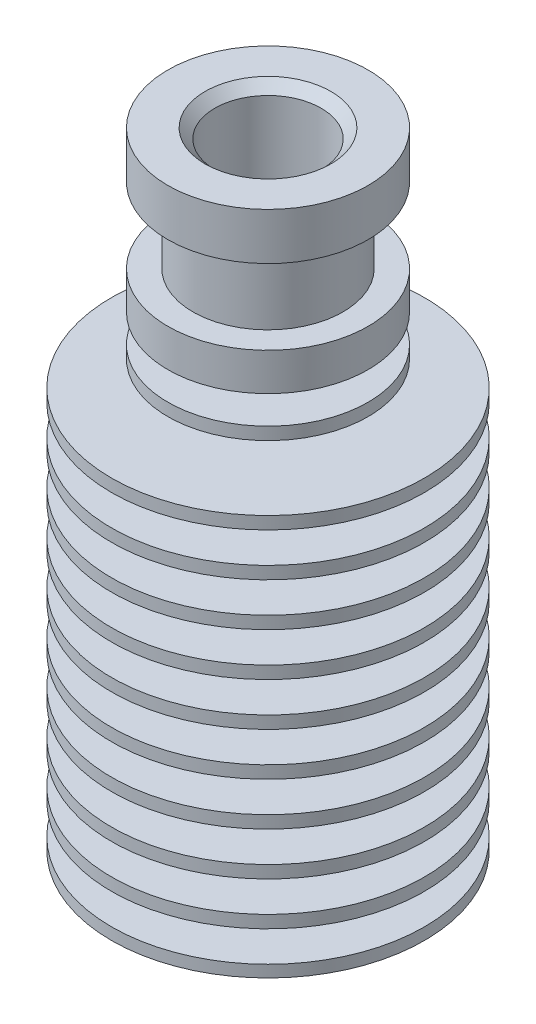
SolidWorks part; units mm, degrees
material "Stop 1060"
ref_plane "Płaszczyzna przednia" through (0, 0, 0) normal (0, 0, 1) x (1, 0, 0)
ref_plane "Płaszczyzna górna" through (0, 0, 0) normal (0, 1, 0) x (1, 0, 0)
ref_plane "Płaszczyzna prawa" through (0, 0, 0) normal (1, 0, 0) x (0, 0, -1)
sketch "Szkic1" plane through (0, 0, 0) normal (0, 0, 1) x (1, 0, 0)
  line L0 (0, 0) -> (-12.5, 0)
  line L1 (-12.5, 0) -> (-12.5, 32)
  line L2 (-12.5, 32) -> (-8, 32)
  line L3 (-8, 32) -> (-8, 50)
  line L4 (-8, 50) -> (0, 50)
  line L5 (0, 50) -> (0, 0)
  line L6 (0, 50) -> (0, 0) construction
  dimension "D1" = 50
  dimension "D2" = 32
  dimension "D3" = 12.5
  dimension "D4" = 8
revolve "Obrót1" add sketch "Szkic1" angle 360 about L6
sketch "Szkic2" plane through (0, 0, 0) normal (0, 0, 1) x (1, 0, 0)
  line L0 (-8, 46.25) -> (-6, 46.25)
  line L1 (-8, 50) -> (-8, 32) construction
  line L2 (0, 46.25) -> (0, 40.25) construction
  line L3 (-6, 40.25) -> (-8, 40.25)
  line L4 (-8, 40.25) -> (-8, 46.25)
  line L5 (8, 50) -> (-8, 50) construction
  line L6 (-6, 46.25) -> (-6, 40.25)
  line L7 (0, 46.25) -> (-6, 46.25) construction
  line L8 (-6, 40.25) -> (0, 40.25) construction
  dimension "D1" = 3.75
  dimension "D2" = 6
  dimension "D3" = 6
revolve "Wycięcie-obrót1" cut sketch "Szkic2" angle 360 about L2
sketch "Szkic3" plane through (0, 0, 0) normal (0, 0, 1) x (1, 0, 0)
  line L0 (-8, 37.25) -> (-4.5, 37.25)
  line L1 (-8, 40.25) -> (-8, 32) construction
  line L2 (-4.5, 37.25) -> (-4.5, 35)
  line L3 (-4.5, 35) -> (-8, 35)
  line L4 (-8, 34) -> (-4.5, 34)
  line L5 (-4.5, 34) -> (-4.5, 32)
  line L6 (12.5, 32) -> (-12.5, 32) construction
  line L7 (-4.5, 32) -> (-8, 32)
  line L8 (-8, 32) -> (-8, 34)
  line L9 (0, 32) -> (0, 40.25) construction
  line L10 (8, 40.25) -> (-8, 40.25) construction
  line L11 (-8, 37.25) -> (-8, 35)
  dimension "D1" = 3
  dimension "D2" = 2.25
  dimension "D3" = 1
  dimension "D4" = 4.5
revolve "Wycięcie-obrót2" cut sketch "Szkic3" angle 360 about L9
sketch "Szkic4" plane through (0, 0, 0) normal (0, 0, 1) x (1, 0, 0)
  line L0 (0, 0) -> (0, 32) construction
  line L1 (12.5, 32) -> (-12.5, 32) construction
  line L2 (-4.5, 31) -> (-12.5, 31)
  line L3 (-12.5, 32) -> (-12.5, 0) construction
  line L4 (-12.5, 31) -> (-12.5, 28.55)
  line L5 (-12.5, 28.55) -> (-4.5, 28.55)
  line L6 (-4.5, 31) -> (-4.5, 28.55)
  line L7 (-4.5, 34) -> (-4.5, 32) construction
  line L8 (-4.5, 31) -> (0, 31) construction
  line L9 (-4.5, 28.55) -> (0, 28.55) construction
  line L10 (-12.5, 25.1) -> (-4.5, 25.1)
  line L11 (-4.5, 27.55) -> (-4.5, 25.1)
  line L12 (-4.5, 27.55) -> (-12.5, 27.55)
  line L13 (-12.5, 27.55) -> (-12.5, 25.1)
  line L14 (-12.5, 21.65) -> (-4.5, 21.65)
  line L15 (-4.5, 24.1) -> (-4.5, 21.65)
  line L16 (-4.5, 24.1) -> (-12.5, 24.1)
  line L17 (-12.5, 24.1) -> (-12.5, 21.65)
  dimension "D1" = 1
  dimension "D2" = 2.45
  dimension "D4" = 3.45
  dimension "D3" = 3
revolve "Wycięcie-obrót3" cut sketch "Szkic4" angle 360 about L0
sketch "Szkic5" plane through (0, 0, 0) normal (0, 0, 1) x (1, 0, 0)
  line L0 (-12.5, 21.65) -> (-12.5, 0) construction
  line L1 (-12.5, 20.65) -> (-6, 20.65)
  line L2 (-12.5, 20.65) -> (-12.5, 18.2)
  line L3 (-12.5, 18.2) -> (-6, 18.2)
  line L4 (-6, 20.65) -> (-6, 18.2)
  line L5 (-6, 20.65) -> (0, 20.65) construction
  line L6 (0, 20.65) -> (0, 18.2) construction
  line L7 (0, 18.2) -> (-6, 18.2) construction
  line L8 (-4.5, 24.1) -> (-4.5, 21.65) construction
  line L9 (0, 0) -> (0, 21.65) construction
  line L10 (12.5, 21.65) -> (-12.5, 21.65) construction
  dimension "D1" = 6
  dimension "D2" = 1
revolve "Wycięcie-obrót4" cut sketch "Szkic5" angle 360 about axis through (0, 50, 0) along (0, 1, 0)
sketch "Szkic6" plane through (0, 0, 0) normal (0, 0, 1) x (1, 0, 0)
  line L0 (-12.5, 18.2) -> (-12.5, 0) construction
  line L1 (-12.5, 17.2) -> (-7, 17.2)
  line L2 (-12.5, 17.2) -> (-12.5, 14.75)
  line L3 (-12.5, 14.75) -> (-7, 14.75)
  line L4 (-7, 17.2) -> (-7, 14.75)
  line L5 (-6, 20.65) -> (-6, 18.2) construction
  line L6 (12.5, 18.2) -> (-12.5, 18.2) construction
  line L7 (0, 0) -> (0, 18.2) construction
  line L8 (-12.5, 11.3) -> (-7, 11.3)
  line L9 (-7, 13.75) -> (-7, 11.3)
  line L10 (-12.5, 13.75) -> (-7, 13.75)
  line L11 (-12.5, 13.75) -> (-12.5, 11.3)
  line L12 (-12.5, 7.85) -> (-7, 7.85)
  line L13 (-7, 10.3) -> (-7, 7.85)
  line L14 (-12.5, 10.3) -> (-7, 10.3)
  line L15 (-12.5, 10.3) -> (-12.5, 7.85)
  line L16 (-12.5, 4.4) -> (-7, 4.4)
  line L17 (-7, 6.85) -> (-7, 4.4)
  line L18 (-12.5, 6.85) -> (-7, 6.85)
  line L19 (-12.5, 6.85) -> (-12.5, 4.4)
  line L20 (-12.5, 0.95) -> (-7, 0.95)
  line L21 (-7, 3.4) -> (-7, 0.95)
  line L22 (-12.5, 3.4) -> (-7, 3.4)
  line L23 (-12.5, 3.4) -> (-12.5, 0.95)
  dimension "D1" = 1
  dimension "D2" = 7
  dimension "D4" = 1
  dimension "D3" = 5
revolve "Wycięcie-obrót5" cut sketch "Szkic6" angle 360 about axis through (0, 50, 0) along (0, 1, 0)
hole_wizard "Otwór gwintowany M61" positions "Szkic8" profile "Szkic9" tap size "M6" standard "ISO"
sketch "Szkic8" plane through (0, 0, 0) normal (0, -1, 0) x (-1, 0, 0)
  point P0 (0, 0)
sketch "Szkic9" plane through (0, 0, 0) normal (1, 0, 0) x (0, 0, -1)
  line L0 (0, 0) -> (0, 29.0022)
  line L1 (0, 29.0022) -> (2.5, 27.5)
  line L2 (2.5, 27.5) -> (2.5, 0.525)
  line L3 (2.5, 0.525) -> (3.025, 0)
  line L5 (3.025, 0) -> (0, 0)
  line L6 (-2.5, 0.525) -> (-3.025, 0) construction
  line L10 (0, 29.0022) -> (-2.5, 27.5) construction
  line L11 (0, -6.35) -> (0, 107.95) construction
  dimension "Średnica wiertła gwintu" = 5
  dimension "Głębokość otworu gwintowanego" = 27.5
  dimension "Średnica zewnętrznego pogłębienia stożkowego" = 6.05
  dimension "Kąt zewnętrznego pogłębienia stożkowego" = 90
  dimension "Kąt wiertła" = 118
cosmetic thread "Gwint otworu1" parameters "D1"=26, "D2"=6
hole_wizard "Otwór gwintowany M102" positions "Szkic12" profile "Szkic13" tap size "M10" standard "ISO"
sketch "Szkic12" plane through (0, 50, 0) normal (0, 1, 0) x (1, 0, 0)
  point P0 (0, 0)
sketch "Szkic13" plane through (0, 50, 0) normal (1, 0, 0) x (0, 0, 1)
  line L0 (0, 0) -> (0, 12.5537)
  line L1 (0, 12.5537) -> (4.25, 10)
  line L2 (4.25, 10) -> (4.25, 0.775)
  line L3 (4.25, 0.775) -> (5.025, 0)
  line L5 (5.025, 0) -> (0, 0)
  line L6 (-4.25, 0.775) -> (-5.025, 0) construction
  line L10 (0, 12.5537) -> (-4.25, 10) construction
  line L11 (0, -6.35) -> (0, 107.95) construction
  dimension "Średnica wiertła gwintu" = 8.5
  dimension "Głębokość otworu gwintowanego" = 10
  dimension "Średnica zewnętrznego pogłębienia stożkowego" = 10.05
  dimension "Kąt zewnętrznego pogłębienia stożkowego" = 90
  dimension "Kąt wiertła" = 118
cosmetic thread "Gwint otworu3" parameters "D1"=7.5, "D2"=10
sketch "Szkic14" plane through (0, 50, 0) normal (0, 1, 0) x (1, 0, 0)
  circle A0 centre (0, 0) radius 0.95
  dimension "D1" = 1.9
extrude "Wytnij-wyciągnięcie1" cut sketch "Szkic14" against normal up to next
